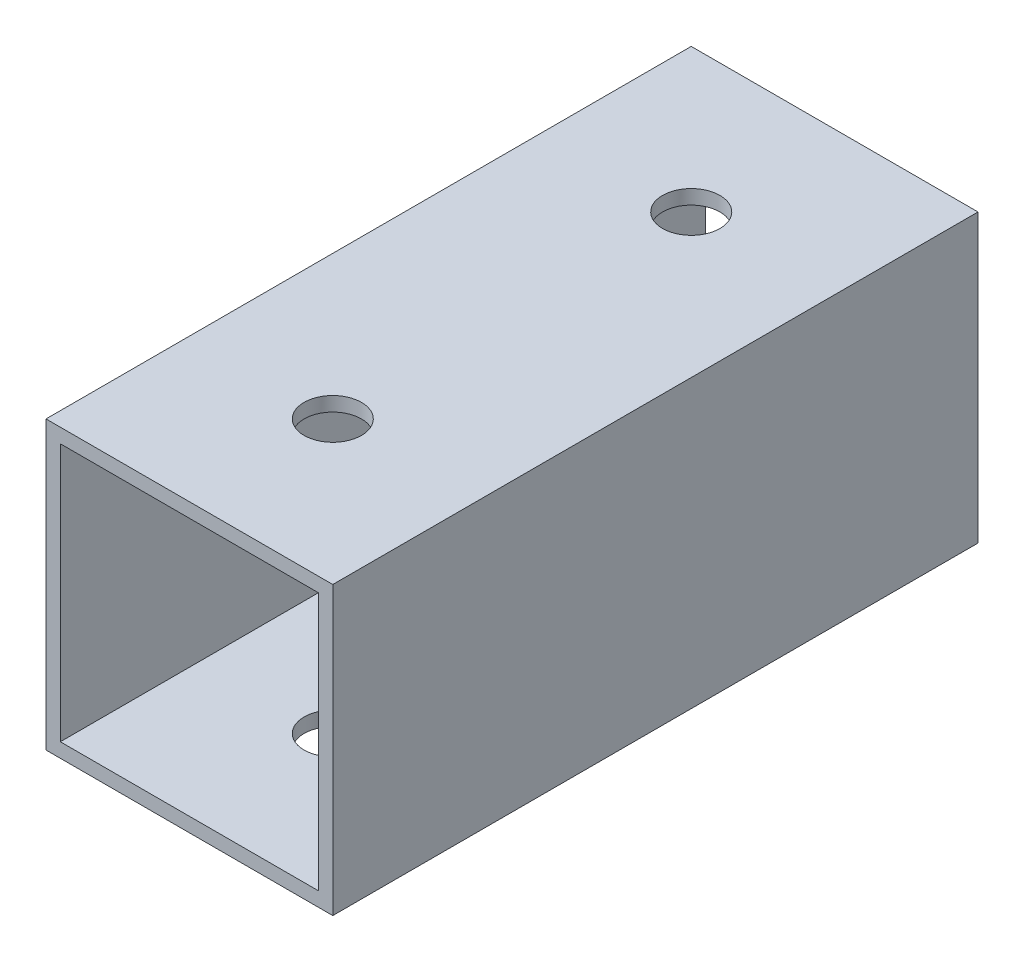
SolidWorks part; units mm, degrees
ref_plane "前视基准面" through (0, 0, 0) normal (0, 0, 1) x (1, 0, 0)
ref_plane "上视基准面" through (0, 0, 0) normal (0, 1, 0) x (1, 0, 0)
ref_plane "右视基准面" through (0, 0, 0) normal (1, 0, 0) x (0, 0, -1)
other "Configuration Table"
sketch "草图1" plane through (0, 0, 0) normal (0, 0, 1) x (1, 0, 0)
  line L1 (-10, 10) -> (10, 10)
  line L2 (-10, 10) -> (-10, -10)
  line L3 (-10, -10) -> (10, -10)
  line L4 (10, 10) -> (10, -10)
  line L5 (-10, 10) -> (10, -10) construction
  line L6 (-10, -10) -> (10, 10) construction
  line L7 (-9, 9) -> (9, 9)
  line L8 (-9, 9) -> (-9, -9)
  line L9 (-9, -9) -> (9, -9)
  line L10 (9, 9) -> (9, -9)
  line L11 (-9, 9) -> (9, -9) construction
  line L12 (-9, -9) -> (9, 9) construction
  point P0 (0, 0)
  point P6 (0, 0)
  dimension "D1" = 1
  dimension "D2" = 20
  dimension "D3" = 20
extrude "凸台-拉伸1" add sketch "草图1" along normal blind 45
sketch "草图2" plane through (0, 10, 0) normal (0, 1, 0) x (1, 0, 0)
  line L0 (0, 0) -> (0, -45) construction
  line L1 (10, 0) -> (-10, 0) construction
  line L2 (10, -45) -> (-10, -45) construction
  circle A0 centre (0, -10) radius 2
  circle A1 centre (0, -35) radius 2
  dimension "D3" = 4
  dimension "D1" = 25
  dimension "D2" = 10
extrude "切除-拉伸1" cut sketch "草图2" against normal up to surface (20 mm away) up to face at (0, -10, 22.5)
